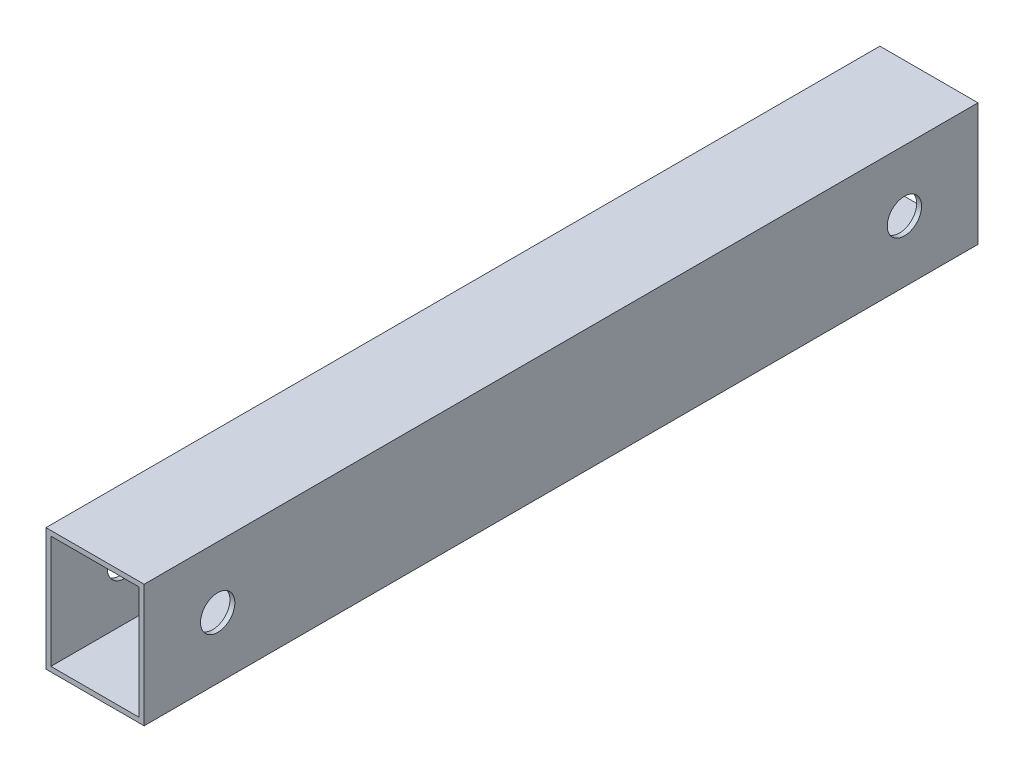
SolidWorks part; units mm, degrees
ref_plane "Front Plane" through (0, 0, 0) normal (0, 0, 1) x (1, 0, 0)
ref_plane "Top Plane" through (0, 0, 0) normal (0, 1, 0) x (1, 0, 0)
ref_plane "Right Plane" through (0, 0, 0) normal (1, 0, 0) x (0, 0, -1)
sketch "Sketch1" plane through (0, 0, 0) normal (0, 0, 1) x (1, 0, 0)
  line L1 (-25.7693, 6.4286) -> (-5.7693, 6.4286)
  line L2 (-25.7693, 6.4286) -> (-25.7693, -18.5714)
  line L3 (-25.7693, -18.5714) -> (-5.7693, -18.5714)
  line L4 (-5.7693, 6.4286) -> (-5.7693, -18.5714)
  dimension "D1" = 20
  dimension "D2" = 25
extrude "Boss-Extrude1" add sketch "Sketch1" along normal blind 170
shell "Shell1" thickness 1
sketch "Sketch2" plane through (-25.7693, 0, 0) normal (-1, 0, 0) x (0, 0, 1)
  line L0 (0, 6.4286) -> (0, -18.5714) construction
  line L1 (170, 6.4286) -> (0, 6.4286) construction
  line L2 (170, 6.4286) -> (170, -18.5714) construction
  circle A0 centre (15, -6.0714) radius 3.5
  circle A1 centre (155, -6.0714) radius 3.5
  dimension "D1" = 7
  dimension "D5" = 15
  dimension "D2" = 15
  dimension "D3" = 12.5
  dimension "D4" = 2
extrude "Cut-Extrude1" cut sketch "Sketch2" against normal blind 170
